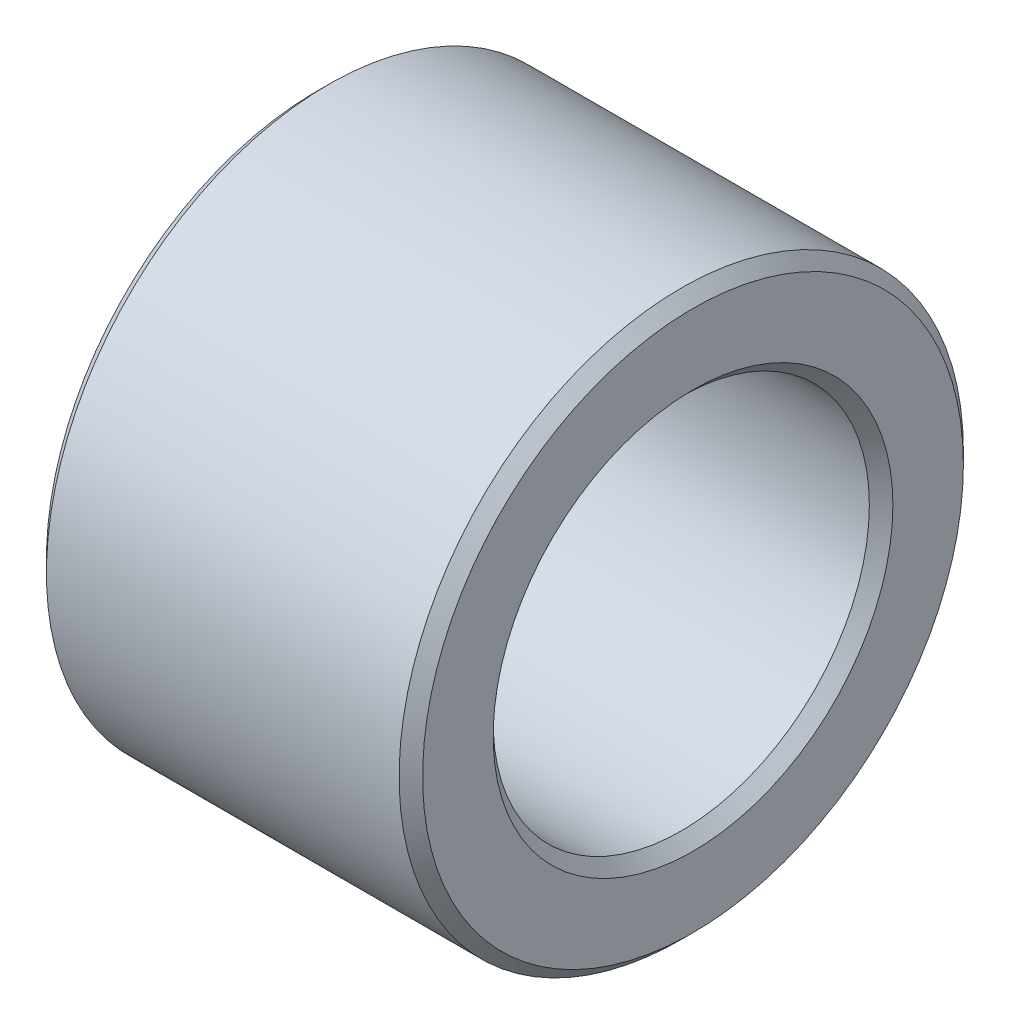
SolidWorks part; units mm, degrees
material "Tin Bearing Bronze"
ref_plane "Front Plane" through (0, 0, 0) normal (0, 0, 1) x (1, 0, 0)
ref_plane "Top Plane" through (0, 0, 0) normal (0, 1, 0) x (1, 0, 0)
ref_plane "Right Plane" through (0, 0, 0) normal (1, 0, 0) x (0, 0, -1)
sketch "Sketch1" plane through (0, 0, 0) normal (1, 0, 0) x (0, 0, -1)
  circle A0 centre (0, 0) radius 4
  circle A1 centre (0, 0) radius 6
  dimension "D1" = 8
  dimension "D2" = 12
extrude "Boss-Extrude1" add sketch "Sketch1" along normal blind 8
chamfer "Chamfer1" distance 0.25 angle 45 4 edges at (0, 0, -6) (0, 0, -4) (8, 0, -6) (8, 0, -4)
